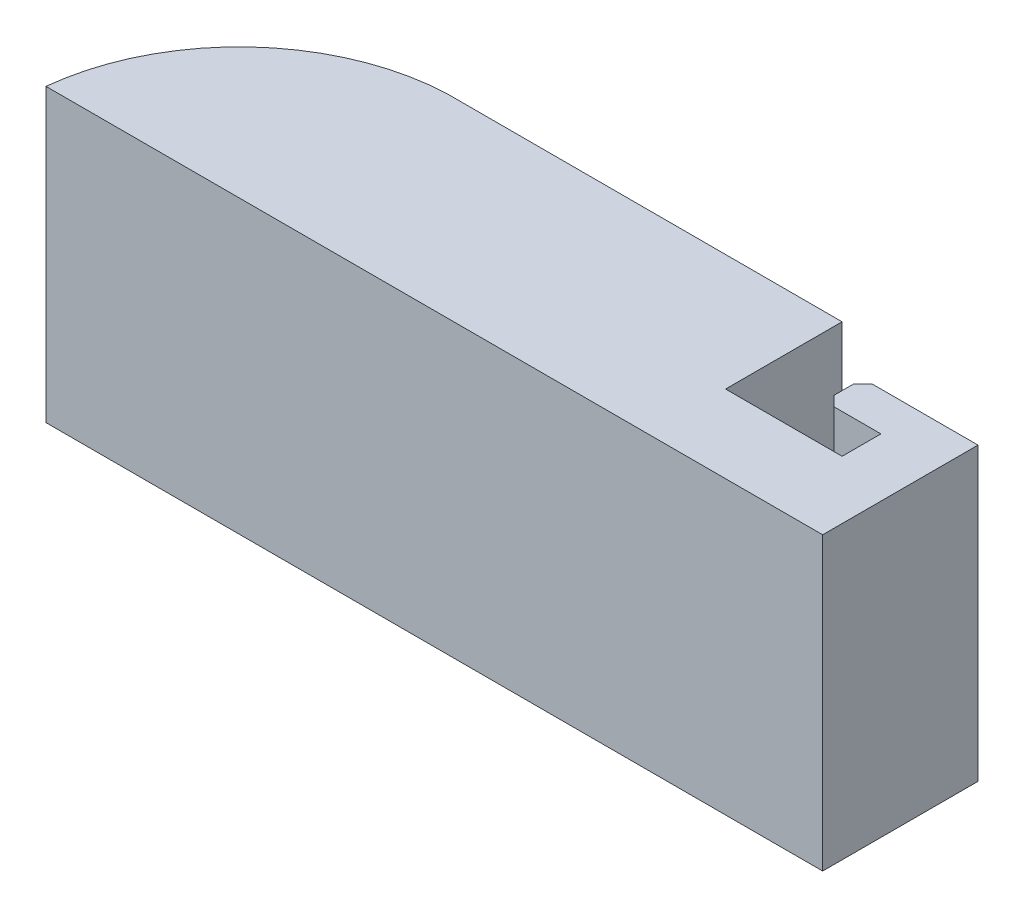
SolidWorks part; units mm, degrees
ref_plane "Front Plane" through (0, 0, 0) normal (0, 0, 1) x (1, 0, 0)
ref_plane "Top Plane" through (0, 0, 0) normal (0, 1, 0) x (1, 0, 0)
ref_plane "Right Plane" through (0, 0, 0) normal (1, 0, 0) x (0, 0, -1)
sketch "Sketch1" plane through (0, 0, 0) normal (0, 1, 0) x (1, 0, 0)
  line L1 (0, 0) -> (40, 0)
  line L2 (0, 0) -> (0, 10)
  line L3 (0, 10) -> (40, 10)
  line L4 (40, 0) -> (40, 10)
  dimension "D1" = 40
  dimension "D2" = 10
extrude "Boss-Extrude1" add sketch "Sketch1" along normal blind 15
sketch "Sketch2" plane through (0, 15, 0) normal (0, 1, 0) x (1, 0, 0)
  line L0 (40, 10) -> (0, 10) construction
  line L1 (10.6638, 10) -> (0, 10)
  line L2 (0, 10) -> (0, 0)
  arc A0 (0, 0) -> (10.6638, 10) centre (11.1116, -1.1634) cw
extrude "Cut-Extrude1" cut sketch "Sketch2" against normal through all
sketch "Sketch3" plane through (0, 15, 0) normal (0, 1, 0) x (1, 0, 0)
  line L0 (40, 10) -> (31, 10)
  line L1 (40, 10) -> (10.6638, 10) construction
  line L2 (31, 10) -> (31, 4)
  line L3 (31, 4) -> (37, 4)
  line L4 (37, 4) -> (37, 6)
  line L5 (37, 6) -> (34.0715, 6)
  line L6 (34.0715, 6) -> (34.0715, 8)
  line L7 (34.0715, 8) -> (40, 8)
  line L8 (40, 0) -> (40, 10) construction
  line L9 (40, 8) -> (40, 10)
  line L10 (0, 0) -> (40, 0) construction
  dimension "D1" = 4
  dimension "D2" = 2
  dimension "D3" = 2
  dimension "D4" = 3
  dimension "D5" = 6
extrude "Cut-Extrude2" cut sketch "Sketch3" against normal through all
chamfer "Chamfer1" distance 0.5 angle 45 2 edges at (34.0715, 7.5, -8) (34.0715, 7.5, -6)
